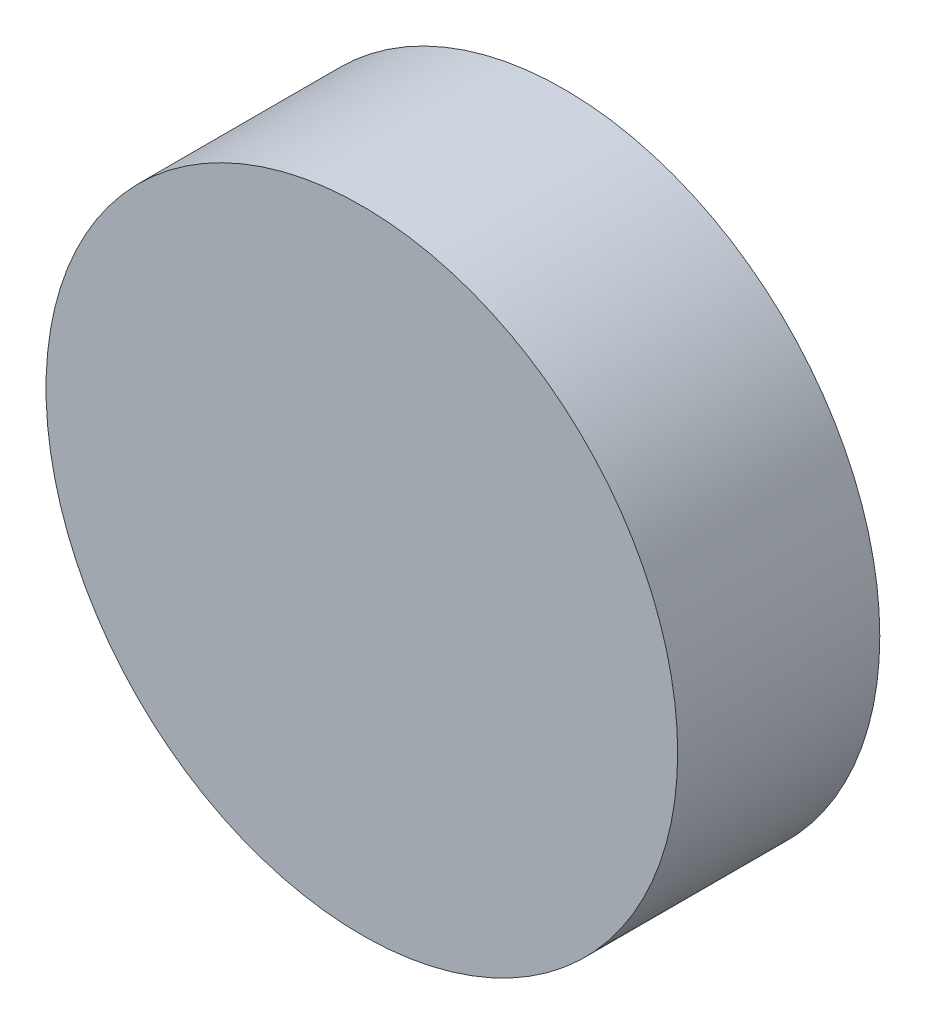
SolidWorks part; units mm, degrees
ref_plane "Plan de face" through (0, 0, 0) normal (0, 0, 1) x (1, 0, 0)
ref_plane "Plan de dessus" through (0, 0, 0) normal (0, 1, 0) x (1, 0, 0)
ref_plane "Plan de droite" through (0, 0, 0) normal (1, 0, 0) x (0, 0, -1)
sketch "Esquisse1" plane through (0, 0, 0) normal (0, 0, 1) x (1, 0, 0)
  circle A0 centre (0, 0) radius 2.5
  dimension "D1" = 5
extrude "Boss.-Extru.1" add sketch "Esquisse1" along normal blind 1.6
